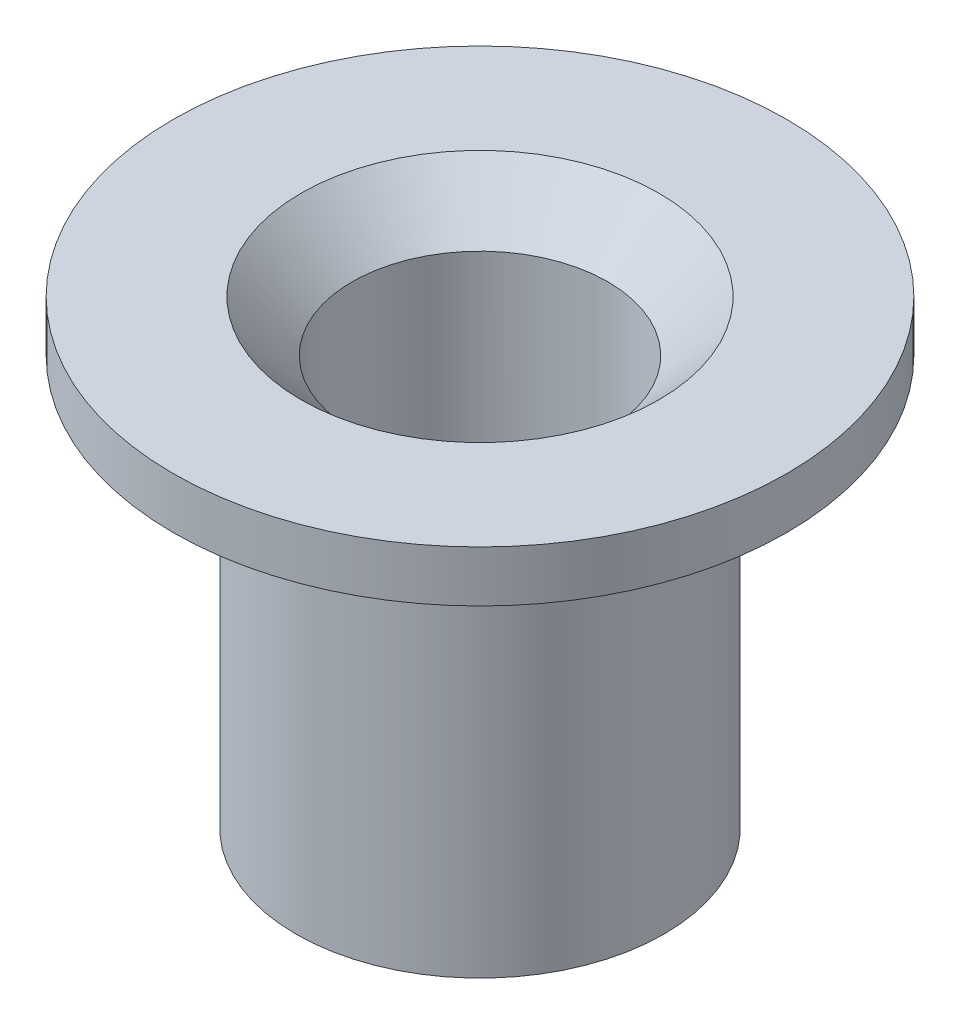
SolidWorks part; units mm, degrees
ref_plane "Front Plane" through (0, 0, 0) normal (0, 0, 1) x (1, 0, 0)
ref_plane "Top Plane" through (0, 0, 0) normal (0, 1, 0) x (1, 0, 0)
ref_plane "Right Plane" through (0, 0, 0) normal (1, 0, 0) x (0, 0, -1)
sketch "Sketch1" plane through (0, 0, 0) normal (1, 0, 0) x (0, 0, -1)
  line L0 (2.5, 9) -> (2.5, 0)
  line L1 (0, 0) -> (6, 0) construction
  line L2 (0, 0) -> (0, 9) construction
  line L3 (0, 9) -> (6, 9) construction
  line L4 (6, 0) -> (6, 9) construction
  line L5 (2.5, 0) -> (3.6, 0)
  line L6 (3.6, 0) -> (3.6, 8)
  line L7 (3.6, 8) -> (6, 8)
  line L8 (6, 8) -> (6, 9)
  line L9 (6, 9) -> (2.5, 9)
  dimension "D1" = 6
  dimension "D2" = 9
  dimension "D3" = 2.5
  dimension "D4" = 3.6
  dimension "D5" = 1
revolve "Revolve1" add sketch "Sketch1" angle 360 about L2
chamfer "Chamfer1" distance 1 angle 45 1 edges at (0, 8, -3.6)
chamfer "Chamfer2" distance 1 angle 45 1 edges at (0, 9, -2.5)
